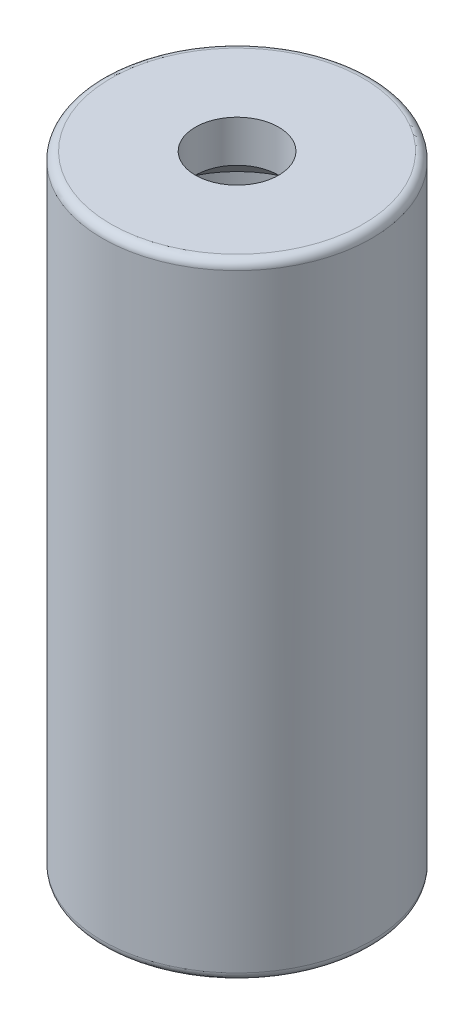
SolidWorks part; units mm, degrees
ref_plane "Front" through (0, 0, 0) normal (0, 0, 1) x (1, 0, 0)
ref_plane "Top" through (0, 0, 0) normal (0, 1, 0) x (1, 0, 0)
ref_plane "Right" through (0, 0, 0) normal (1, 0, 0) x (0, 0, -1)
sketch "Sketch1" plane through (0, 0, 0) normal (0, 1, 0) x (1, 0, 0)
  circle A0 centre (0, 0) radius 16.15
  circle A1 centre (0, 0) radius 11.15
  dimension "D1" = 32.3
  dimension "D2" = 5
extrude "Boss-Extrude1" add sketch "Sketch1" along normal blind 60
sketch "Sketch2" plane through (0, 0, 0) normal (0, -1, 0) x (1, 0, 0)
  circle A1 centre (0, 0) radius 16.15 construction
  circle A2 centre (0, 0) radius 16.15
extrude "Boss-Extrude2" add sketch "Sketch2" along normal blind 5
sketch "Sketch3" plane through (0, 0, 0) normal (0, 0, 1) x (1, 0, 0)
  line L0 (0, 60) -> (0, -5) construction
  line L1 (11.15, 60) -> (-11.15, 60) construction
  line L2 (-16.15, -5) -> (16.15, -5) construction
  line L3 (-11.15, 60) -> (-5, 65)
  line L4 (16.15, 60) -> (-16.15, 60) construction
  line L5 (-5, 65) -> (-5, 70)
  line L6 (-5, 70) -> (-16.15, 70)
  line L7 (-16.15, 70) -> (-16.15, 60)
  line L8 (-16.15, 60) -> (-11.15, 60)
  line L9 (0, 60) -> (0, 82.273) construction
  dimension "D1" = 10
  dimension "D2" = 5
  dimension "D3" = 5
revolve "Revolve1" add sketch "Sketch3" angle 360 about L0
fillet "Fillet1" radius 1 2 edges at (0, 70, 16.15) (0, -5, -16.15)
